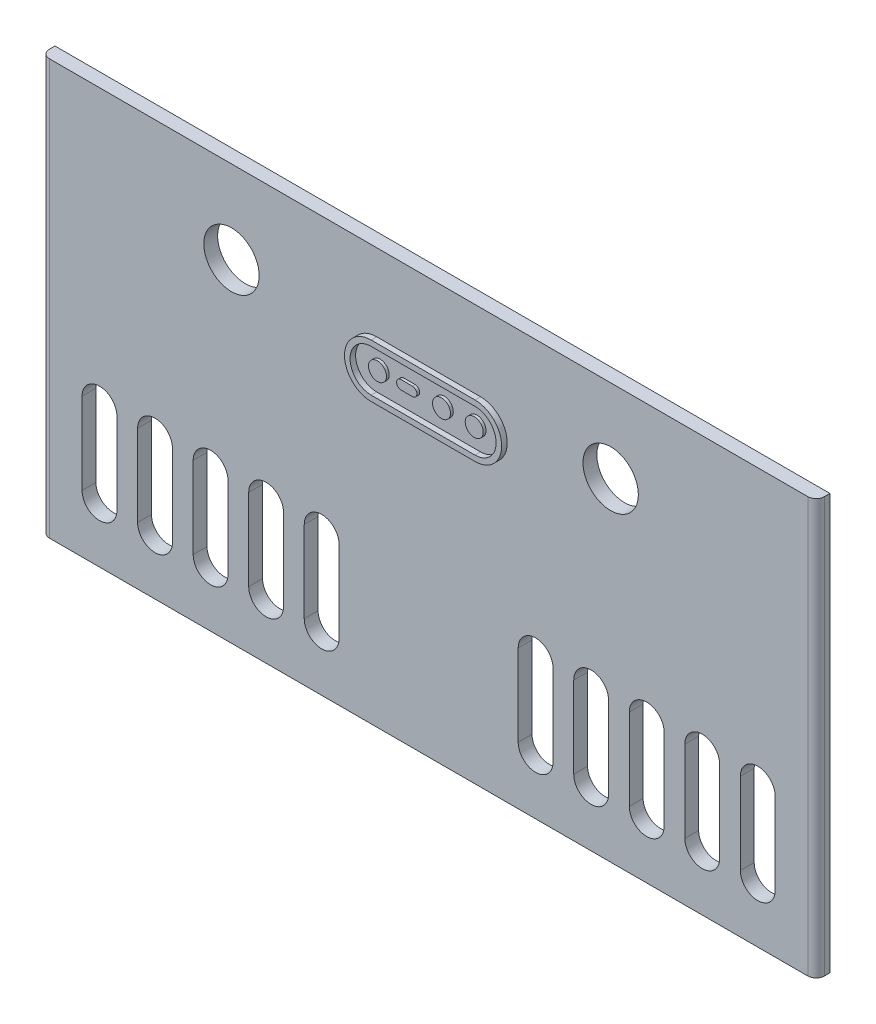
SolidWorks part; units mm, degrees
material "2024-T361"
ref_plane "Front Plane" through (0, 0, 0) normal (0, 0, 1) x (1, 0, 0)
ref_plane "Top Plane" through (0, 0, 0) normal (0, 1, 0) x (1, 0, 0)
ref_plane "Right Plane" through (0, 0, 0) normal (1, 0, 0) x (0, 0, -1)
sketch "Sketch1" plane through (0, 0, 0) normal (0, 0, 1) x (1, 0, 0)
  line L0 (0, 33.8782) -> (0, -47.5565) construction
  line L1 (-140, 75) -> (140, 75)
  line L2 (-140, 75) -> (-140, -75)
  line L3 (-140, -75) -> (140, -75)
  line L4 (140, 75) -> (140, -75)
  line L5 (-25.3568, 0) -> (37.9813, 0) construction
  dimension "D1" = 150
  dimension "D2" = 280
extrude "Boss-Extrude1" add sketch "Sketch1" along normal blind 5
fillet "Fillet1" radius 3 2 edges at (-140, 0, 5) (140, 0, 5)
sketch "Sketch2" plane through (0, 0, 5) normal (0, 0, 1) x (1, 0, 0)
  line L0 (0, -75) -> (0, 75) construction
  line L1 (137, 75) -> (-137, 75) construction
  line L2 (0, 0) -> (0, 75) construction
  line L3 (-137, -75) -> (137, -75) construction
  line L4 (0, 0) -> (0, 75) construction
  line L5 (0, 75) -> (0, 37.5) construction
  line L6 (0, 37.5) -> (-18.7602, 37.5) construction
  line L7 (0, 37.5) -> (18.7602, 37.5) construction
  line L8 (-18.7602, 37.5) -> (18.7602, 37.5) construction
  line L9 (-18.7602, 47.1246) -> (18.7602, 47.1246)
  line L10 (-18.7602, 27.8754) -> (18.7602, 27.8754)
  line L11 (-18.7602, 45.1246) -> (18.7602, 45.1246)
  line L12 (-18.7602, 29.8754) -> (18.7602, 29.8754)
  arc A0 (-18.7602, 47.1246) -> (-18.7602, 27.8754) centre (-18.7602, 37.5) ccw
  arc A1 (18.7602, 27.8754) -> (18.7602, 47.1246) centre (18.7602, 37.5) ccw
  arc A2 (18.7602, 29.8754) -> (18.7602, 45.1246) centre (18.7602, 37.5) ccw
  arc A3 (-18.7602, 45.1246) -> (-18.7602, 29.8754) centre (-18.7602, 37.5) ccw
  point P3 (0, 37.5)
  dimension "D1" = 2
extrude "Boss-Extrude2" add sketch "Sketch2" along normal blind 2
sketch "Sketch3" plane through (0, 0, 5) normal (0, 0, 1) x (1, 0, 0)
  line L0 (-26.3848, 37.5) -> (26.3848, 37.5) construction
  arc A0 (-18.7602, 45.1246) -> (-18.7602, 29.8754) centre (-18.7602, 37.5) ccw construction
  arc A1 (18.7602, 29.8754) -> (18.7602, 45.1246) centre (18.7602, 37.5) ccw construction
sketch "Sketch4" plane through (0, 0, 5) normal (0, 0, 1) x (1, 0, 0)
  line L0 (-26.3848, 37.5) -> (26.3848, 37.5) construction
  line L1 (-8.9352, 37.5) -> (-4.8804, 37.5) construction
  line L2 (-8.9352, 39.1347) -> (-4.8804, 39.1347)
  line L3 (-8.9352, 35.8653) -> (-4.8804, 35.8653)
  circle A0 centre (17.4705, 37.5) radius 3.25
  circle A1 centre (-17.4898, 37.5) radius 3.25
  circle A2 centre (5.6522, 37.5) radius 3.25
  arc A3 (-8.9352, 39.1347) -> (-8.9352, 35.8653) centre (-8.9352, 37.5) ccw
  arc A4 (-4.8804, 35.8653) -> (-4.8804, 39.1347) centre (-4.8804, 37.5) ccw
  point P10 (-6.9078, 37.5)
  dimension "D1" = 6.5
extrude "Boss-Extrude3" add sketch "Sketch4" along normal blind 1
sketch "Sketch5" plane through (0, 0, 5) normal (0, 0, 1) x (1, 0, 0)
  line L0 (-137, 0) -> (137, 0) construction
  line L1 (-137, 75) -> (-137, -75) construction
  line L2 (137, -75) -> (137, 75) construction
  line L3 (0, 0) -> (0, -75) construction
  line L4 (-137, -75) -> (137, -75) construction
  line L77 (118.9148, -24.6773) -> (118.9148, -54.1576) construction
  line L78 (125.2084, -24.6773) -> (125.2084, -54.1576)
  line L98 (112.6213, -24.6773) -> (112.6213, -54.1576)
  line L99 (98.8488, -24.6773) -> (98.8488, -54.1576) construction
  line L100 (105.1424, -24.6773) -> (105.1424, -54.1576)
  line L119 (92.5553, -24.6773) -> (92.5553, -54.1576)
  line L120 (78.7828, -24.6773) -> (78.7828, -54.1576) construction
  line L121 (85.0764, -24.6773) -> (85.0764, -54.1576)
  line L122 (72.4893, -24.6773) -> (72.4893, -54.1576)
  line L123 (58.7168, -24.6773) -> (58.7168, -54.1576) construction
  line L124 (65.0104, -24.6773) -> (65.0104, -54.1576)
  line L125 (52.4233, -24.6773) -> (52.4233, -54.1576)
  line L126 (38.6508, -24.6773) -> (38.6508, -54.1576) construction
  line L127 (44.9444, -24.6773) -> (44.9444, -54.1576)
  line L128 (32.3573, -24.6773) -> (32.3573, -54.1576)
  arc A0 (125.2084, -24.6773) -> (112.6213, -24.6773) centre (118.9148, -24.6773) ccw
  arc A1 (112.6213, -54.1576) -> (125.2084, -54.1576) centre (118.9148, -54.1576) ccw
  arc A2 (105.1424, -24.6773) -> (92.5553, -24.6773) centre (98.8488, -24.6773) ccw
  arc A3 (92.5553, -54.1576) -> (105.1424, -54.1576) centre (98.8488, -54.1576) ccw
  arc A4 (85.0764, -24.6773) -> (72.4893, -24.6773) centre (78.7828, -24.6773) ccw
  arc A5 (72.4893, -54.1576) -> (85.0764, -54.1576) centre (78.7828, -54.1576) ccw
  arc A6 (65.0104, -24.6773) -> (52.4233, -24.6773) centre (58.7168, -24.6773) ccw
  arc A7 (52.4233, -54.1576) -> (65.0104, -54.1576) centre (58.7168, -54.1576) ccw
  arc A8 (44.9444, -24.6773) -> (32.3573, -24.6773) centre (38.6508, -24.6773) ccw
  arc A9 (32.3573, -54.1576) -> (44.9444, -54.1576) centre (38.6508, -54.1576) ccw
  point P13 (118.9148, -39.4175)
  point P22 (98.8488, -39.4175)
  point P29 (78.7828, -39.4175)
  point P36 (58.7168, -39.4175)
  point P43 (38.6508, -39.4175)
extrude "Cut-Extrude1" cut sketch "Sketch5" along a picked direction on the side against the normal blind 5
ref_plane "Plane1" through (0, 0, 0) normal (1, 0, 0) x (0, 0, -1)
mirror "Mirror1" about plane through (0, 0, 0) normal (1, 0, 0) of "Cut-Extrude1"
sketch "Sketch6" plane through (0, 0, 5) normal (0, 0, 1) x (1, 0, 0)
  line L0 (-5.47, 45) -> (137, 45) construction
  line L1 (137, -75) -> (137, 75) construction
  line L2 (137, 45) -> (65.765, 45) construction
  line L3 (-5.47, 45) -> (-137, 45) construction
  line L4 (-137, 75) -> (-137, -75) construction
  line L5 (-137, 45) -> (-71.235, 45) construction
  line L6 (137, 75) -> (-137, 75) construction
  circle A2 centre (65.765, 45) radius 10
  circle A3 centre (-71.235, 45) radius 10
  dimension "D1" = 20
  dimension "D2" = 20
  dimension "D3" = 30
extrude "Cut-Extrude2" cut sketch "Sketch6" against normal up to next
